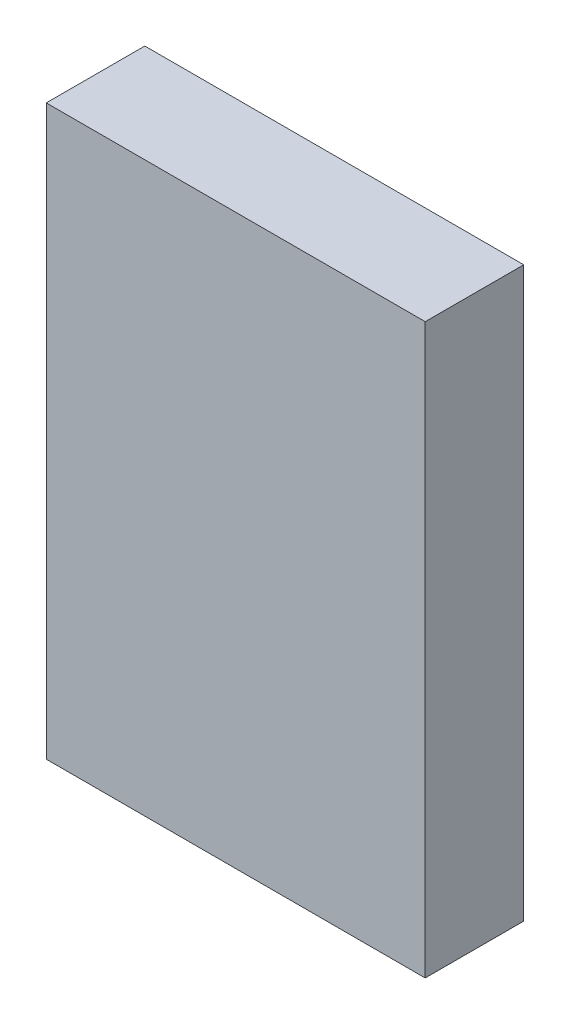
SolidWorks part; units mm, degrees
ref_plane "Front Plane" through (0, 0, 0) normal (0, 0, 1) x (1, 0, 0)
ref_plane "Top Plane" through (0, 0, 0) normal (0, 1, 0) x (1, 0, 0)
ref_plane "Right Plane" through (0, 0, 0) normal (1, 0, 0) x (0, 0, -1)
sketch "Sketch1" plane through (0, 0, 0) normal (0, 0, 1) x (1, 0, 0)
  line L1 (-5, -7.5) -> (5, -7.5)
  line L2 (-5, -7.5) -> (-5, 7.5)
  line L3 (-5, 7.5) -> (5, 7.5)
  line L4 (5, -7.5) -> (5, 7.5)
  line L5 (-5, -7.5) -> (5, 7.5) construction
  line L6 (-5, 7.5) -> (5, -7.5) construction
  point P0 (0, 0)
  dimension "D1" = 15
  dimension "D2" = 10
extrude "Boss-Extrude1" add sketch "Sketch1" along normal blind 2.6
